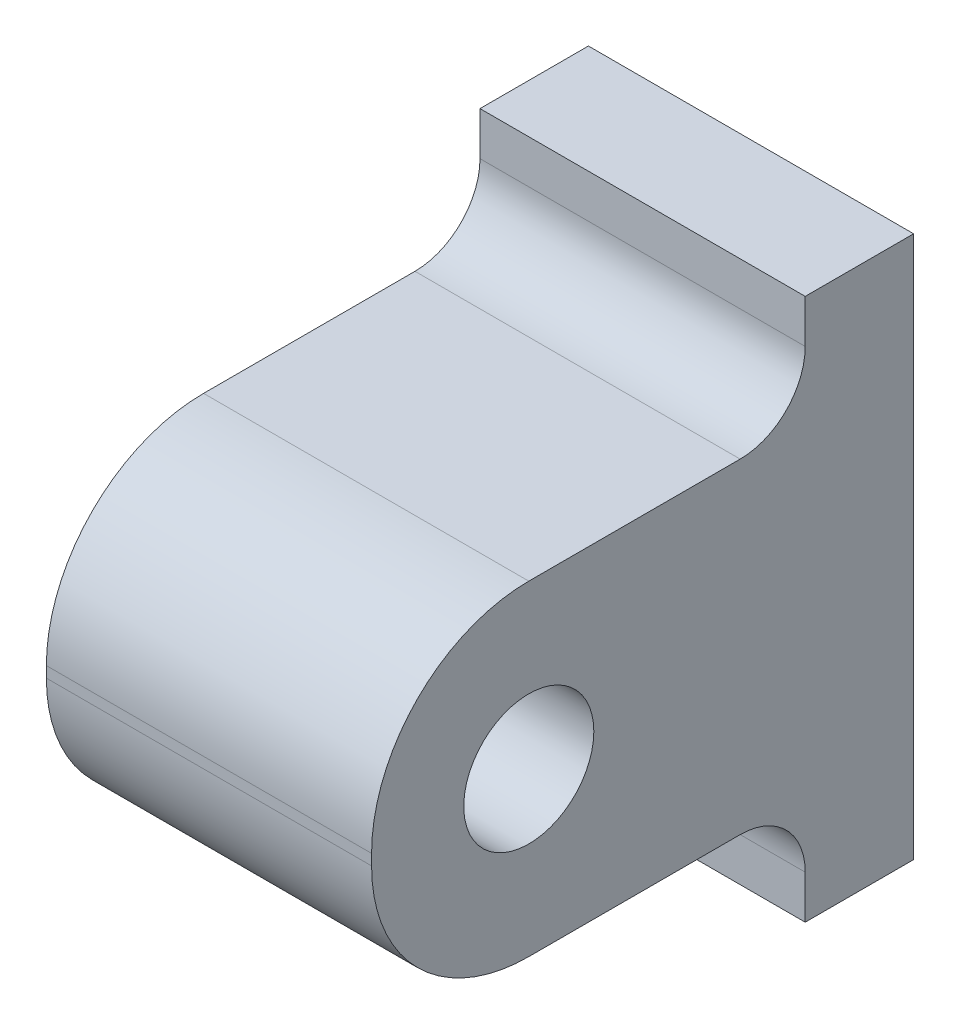
SolidWorks part; units mm, degrees
ref_plane "Plano frontal" through (0, 0, 0) normal (0, 0, 1) x (1, 0, 0)
ref_plane "Plano superior" through (0, 0, 0) normal (0, 1, 0) x (1, 0, 0)
ref_plane "Plano direito" through (0, 0, 0) normal (1, 0, 0) x (0, 0, -1)
sketch "Esboço3" plane through (0, 0, 0) normal (1, 0, 0) x (0, 0, -1)
  line L0 (42.2488, -47.335) -> (42.2488, 2.665)
  line L1 (42.2488, 2.665) -> (32.2488, 2.665)
  line L2 (32.2488, 2.665) -> (32.2488, -1.335)
  line L3 (42.2488, -47.335) -> (32.2488, -47.335)
  line L4 (32.2488, -47.335) -> (32.2488, -43.335)
  line L5 (26.2488, -37.335) -> (6.7488, -37.335)
  line L6 (-7.7512, -22.835) -> (-7.7512, -21.835)
  line L7 (6.7488, -7.335) -> (26.2488, -7.335)
  arc A0 (-7.7512, -22.835) -> (6.7488, -37.335) centre (6.7488, -22.835) ccw
  arc A1 (-7.7512, -21.835) -> (6.7488, -7.335) centre (6.7488, -21.835) cw
  arc A2 (32.2488, -1.335) -> (26.2488, -7.335) centre (26.2488, -1.335) cw
  arc A3 (26.2488, -37.335) -> (32.2488, -43.335) centre (26.2488, -43.335) cw
extrude "Ressalto-extrusão2" add sketch "Esboço3" against normal blind 30
sketch "Esboço5" plane through (0, 0, 0) normal (1, 0, 0) x (0, 0, -1)
  circle A0 centre (6.7488, -22.335) radius 6
extrude "Corte-extrusão1" cut sketch "Esboço5" against normal blind 30 contours A0
sketch "Esboço2" plane through (0, 0, 0) normal (1, 0, 0) x (0, 0, -1)
